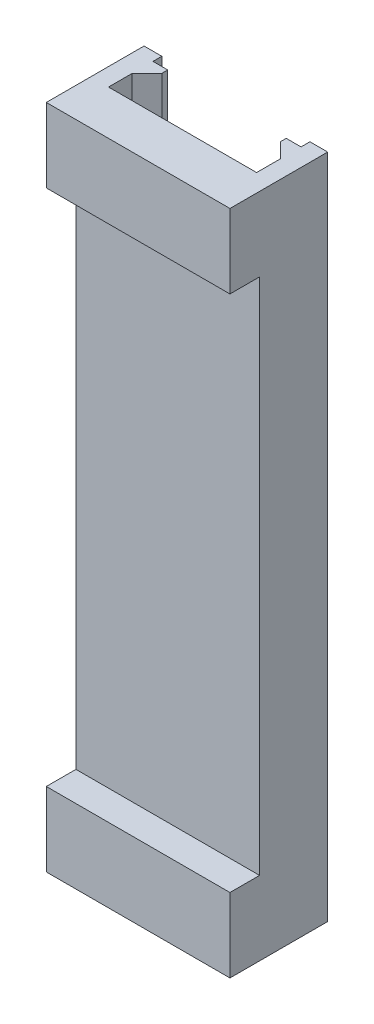
SolidWorks part; units mm, degrees
ref_plane "Přední rovina" through (0, 0, 0) normal (0, 0, 1) x (1, 0, 0)
ref_plane "Horní rovina" through (0, 0, 0) normal (0, 1, 0) x (1, 0, 0)
ref_plane "Pravá rovina" through (0, 0, 0) normal (1, 0, 0) x (0, 0, -1)
sketch "Skica1" plane through (0, 0, 0) normal (0, 1, 0) x (1, 0, 0)
  line L0 (-5, 0) -> (5, 0)
  line L1 (0, -1000) -> (0, 49000) construction
  line L2 (-5, 0) -> (-5, 1.6)
  line L3 (-5, 1.6) -> (-4, 2.6)
  line L4 (-4, 2.6) -> (-4, 3)
  line L6 (-6.2, 3.6) -> (-6.2, -1)
  line L7 (-6.2, -1) -> (6.2, -1)
  line L8 (0, -1) -> (0, 0) construction
  line L9 (-4, 3) -> (-5, 3)
  line L10 (-5, 3) -> (-5, 3.6)
  line L11 (-5, 3.6) -> (-6.2, 3.6)
  line L12 (5, 0) -> (5, 1.6)
  line L13 (5, 1.6) -> (4, 2.6)
  line L14 (4, 2.6) -> (4, 3)
  line L15 (4, 3) -> (5, 3)
  line L16 (5, 3) -> (5, 3.6)
  line L17 (6.2, 3.6) -> (6.2, -1)
  line L18 (5, 3.6) -> (6.2, 3.6)
  dimension "D2" = 0.4
  dimension "D1" = 5
  dimension "D3" = 1
  dimension "D4" = 1.2
  dimension "D5" = 1
  dimension "D6" = 1.6
  dimension "D7" = 1
  dimension "D8" = 0.6
extrude "Přidat vysunutím1" add sketch "Skica1" along normal blind 45
ref_plane "Rovina5" through (6.2, 45, 1) normal (1, 0, 0) x (0, 0, -1)
sketch "Skica3" plane through (0, 0, 1) normal (0, 0, 1) x (1, 0, 0)
  line L0 (6.2, 41.59) -> (6.2, 48.41) construction
  line L1 (-6.2, 45) -> (6.2, 45)
  line L2 (-6.2, 45) -> (-6.2, 40)
  line L3 (-6.2, 40) -> (6.2, 40)
  line L4 (6.2, 45) -> (6.2, 40)
  line L5 (6.2, 45) -> (6.2, 0) construction
  line L6 (-6.2, 0) -> (6.2, 0)
  line L7 (-6.2, 0) -> (-6.2, 5)
  line L8 (-6.2, 5) -> (6.2, 5)
  line L9 (6.2, 0) -> (6.2, 5)
  dimension "D1" = 5
  dimension "D2" = 5
extrude "Přidat vysunutím2" add sketch "Skica3" along normal blind 2
